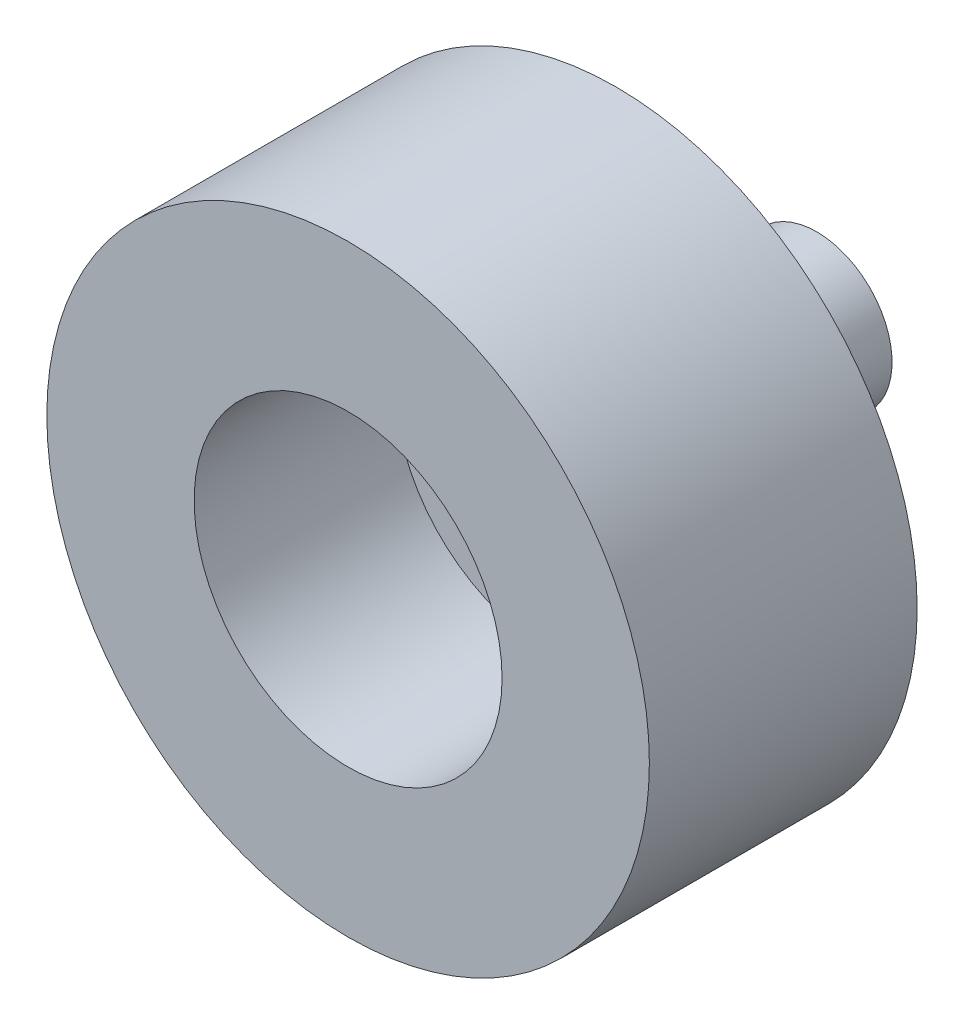
SolidWorks part; units mm, degrees
ref_plane "Plano frontal" through (0, 0, 0) normal (0, 0, 1) x (1, 0, 0)
ref_plane "Plano superior" through (0, 0, 0) normal (0, 1, 0) x (1, 0, 0)
ref_plane "Plano direito" through (0, 0, 0) normal (1, 0, 0) x (0, 0, -1)
sketch "Esboço2" plane through (0, 0, 0) normal (0, 0, 1) x (1, 0, 0)
  circle A0 centre (0, 0) radius 4.5
  dimension "D1" = 9
extrude "Ressalto-extrusão1" add sketch "Esboço2" along normal blind 1
sketch "Esboço3" plane through (0, 0, 0) normal (0, 0, -1) x (-1, 0, 0)
  circle A0 centre (0, 0) radius 1.125
  dimension "D1" = 2.25
extrude "Ressalto-extrusão2" add sketch "Esboço3" along normal blind 3
sketch "Esboço4" plane through (0, 0, 1) normal (0, 0, 1) x (1, 0, 0)
  circle A0 centre (0, 0) radius 2.3
  circle A1 centre (0, 0) radius 4.5 construction
  circle A2 centre (0, 0) radius 4.5
  dimension "D1" = 4.6
extrude "Ressalto-extrusão3" add sketch "Esboço4" along normal blind 3
sketch "Esboço5" plane through (0, 0, 1) normal (0, 0, 1) x (1, 0, 0)
  circle A1 centre (0, 0) radius 2.3
  circle A2 centre (0, 0) radius 2.3
  dimension "D1" = 0
